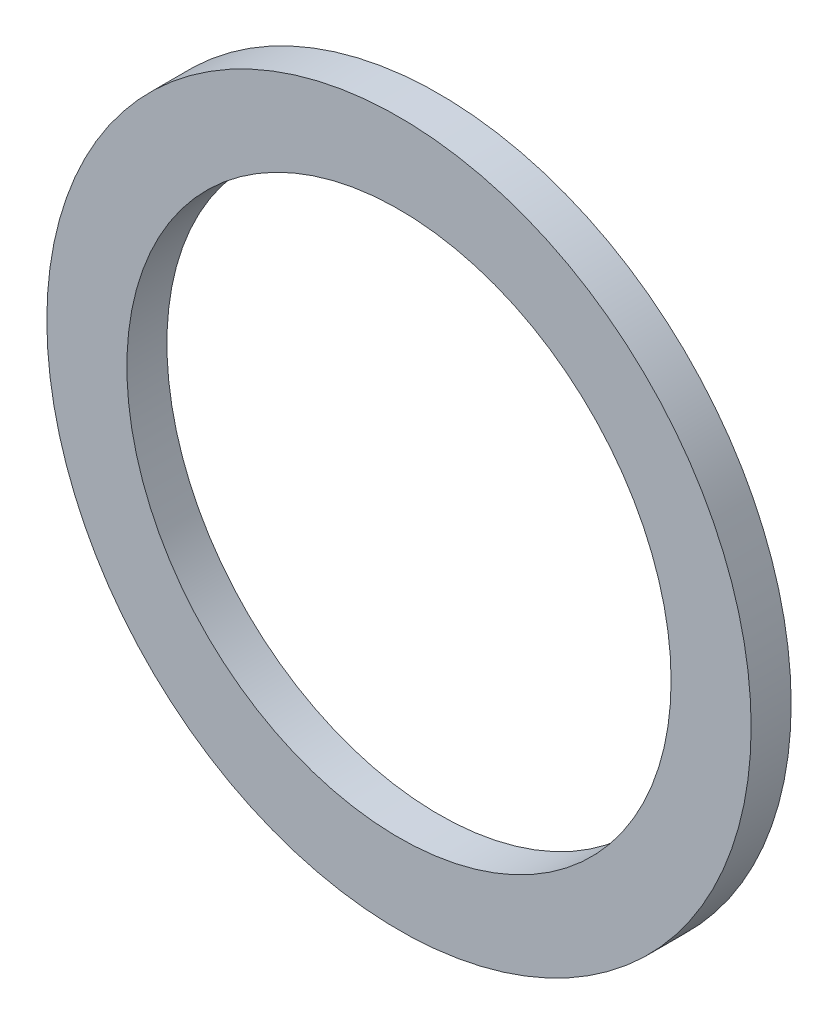
SolidWorks part; units mm, degrees
material "Mahogany"
ref_plane "Front Plane" through (0, 0, 0) normal (0, 0, 1) x (1, 0, 0)
ref_plane "Top Plane" through (0, 0, 0) normal (0, 1, 0) x (1, 0, 0)
ref_plane "Right Plane" through (0, 0, 0) normal (1, 0, 0) x (0, 0, -1)
sketch "Sketch1" plane through (0, 0, 0) normal (0, 0, 1) x (1, 0, 0)
  circle A0 centre (0, 0) radius 86.36
  circle A1 centre (0, 0) radius 111.76
  dimension "D1" = 172.72
  dimension "D2" = 25.4
extrude "Boss-Extrude1" add sketch "Sketch1" along normal blind 12.7 contours A1 A0
